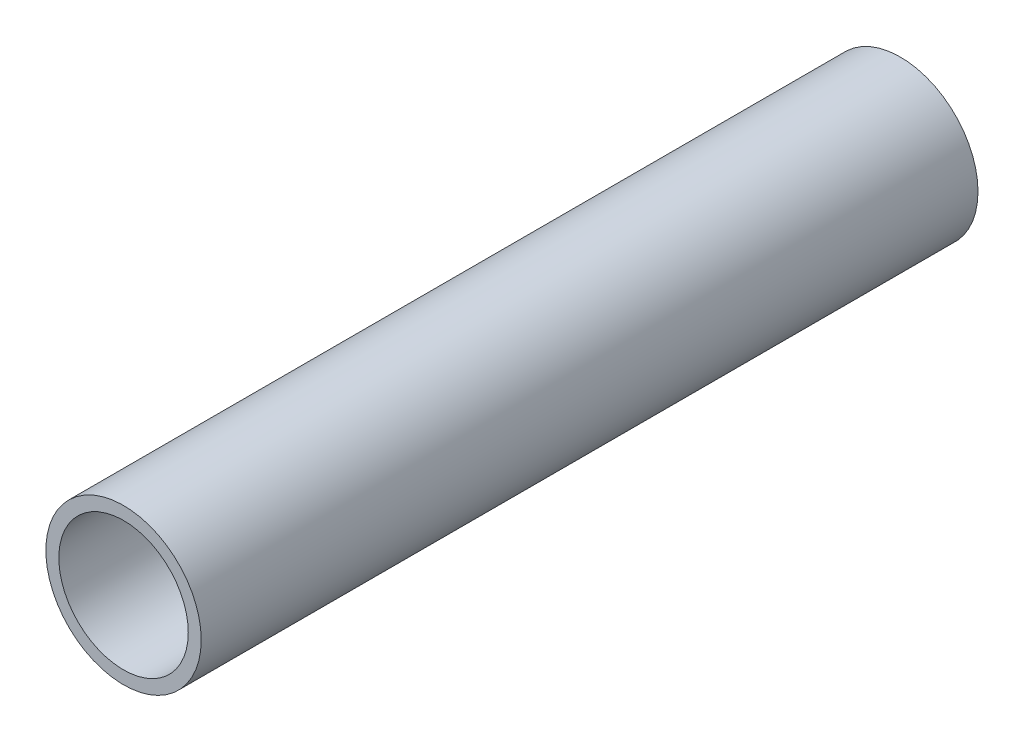
SolidWorks part; units mm, degrees
ref_plane "前视基准面" through (0, 0, 0) normal (0, 0, 1) x (1, 0, 0)
ref_plane "上视基准面" through (0, 0, 0) normal (0, 1, 0) x (1, 0, 0)
ref_plane "右视基准面" through (0, 0, 0) normal (1, 0, 0) x (0, 0, -1)
sketch "草图1" plane through (0, 0, 0) normal (0, 0, 1) x (1, 0, 0)
  circle A0 centre (0, 0) radius 5
  circle A1 centre (0, 0) radius 6
  dimension "D1" = 10
  dimension "D2" = 12
extrude "凸台-拉伸1" add sketch "草图1" along normal blind 60
